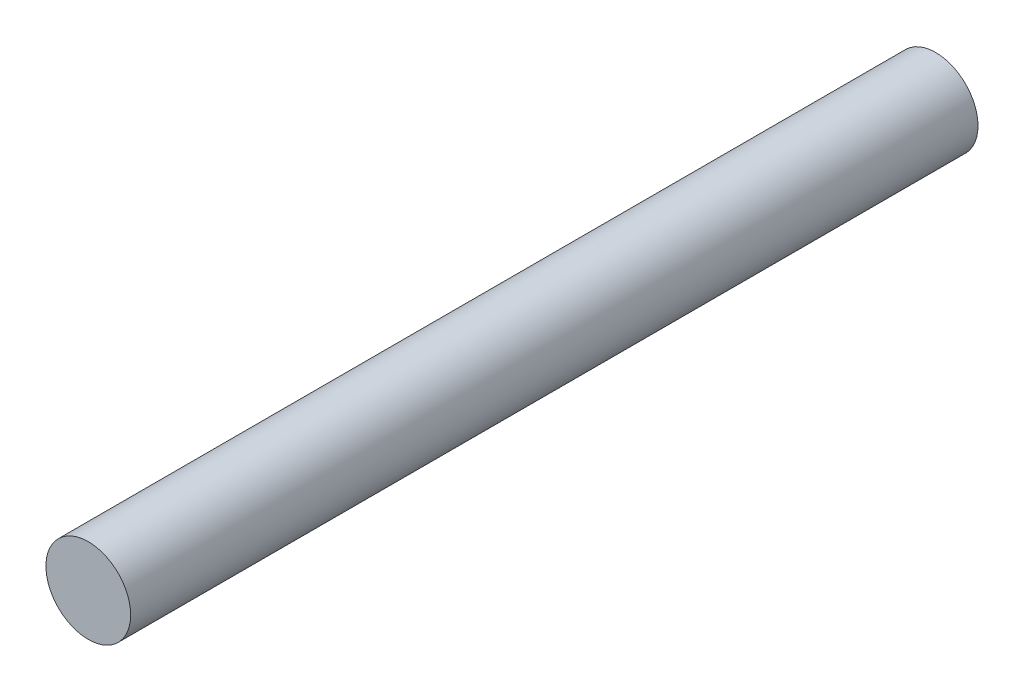
SolidWorks part; units mm, degrees
ref_plane "Front Plane" through (0, 0, 0) normal (0, 0, 1) x (1, 0, 0)
ref_plane "Top Plane" through (0, 0, 0) normal (0, 1, 0) x (1, 0, 0)
ref_plane "Right Plane" through (0, 0, 0) normal (1, 0, 0) x (0, 0, -1)
sketch "Sketch1" plane through (0, 0, 0) normal (0, 0, 1) x (1, 0, 0)
  circle A0 centre (0, 0) radius 0.5
extrude "Boss-Extrude1" add sketch "Sketch1" along normal blind 10
